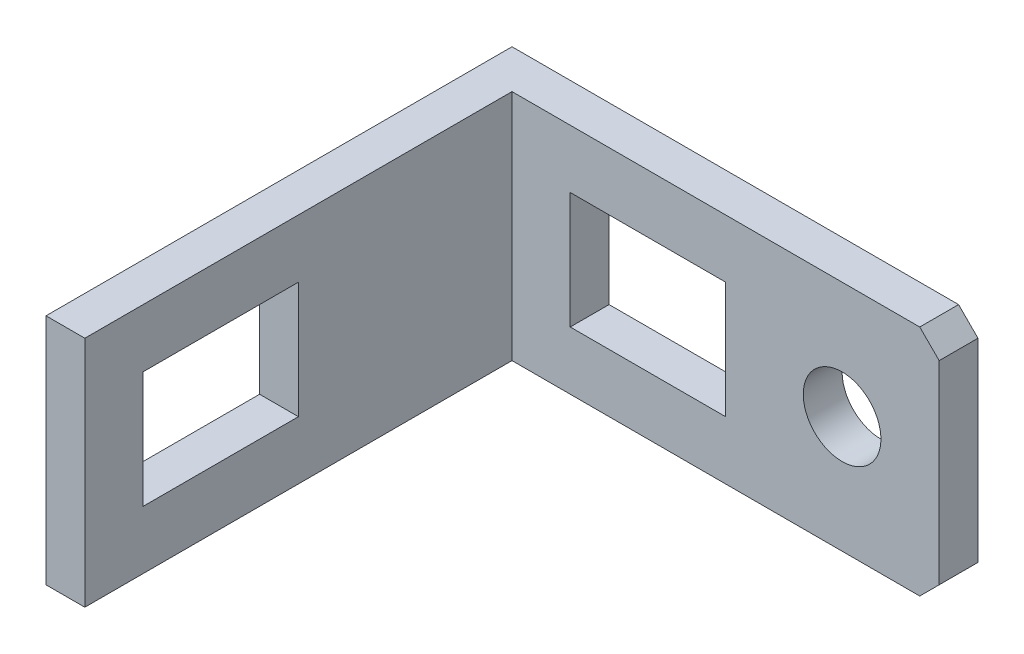
SolidWorks part; units mm, degrees
material "6061-T6 (SS)"
ref_plane "Front Plane" through (0, 0, 0) normal (0, 0, 1) x (1, 0, 0)
ref_plane "Top Plane" through (0, 0, 0) normal (0, 1, 0) x (1, 0, 0)
ref_plane "Right Plane" through (0, 0, 0) normal (1, 0, 0) x (0, 0, -1)
sketch "Sketch1" plane through (0, 0, 0) normal (0, 1, 0) x (1, 0, 0)
  line L1 (38.1, 3.175) -> (-38.1, 3.175)
  line L2 (38.1, 3.175) -> (38.1, -3.175)
  line L3 (38.1, -3.175) -> (-38.1, -3.175)
  line L4 (-38.1, 3.175) -> (-38.1, -3.175)
  line L5 (38.1, 3.175) -> (-38.1, -3.175) construction
  line L6 (38.1, -3.175) -> (-38.1, 3.175) construction
  line L7 (-31.75, -3.175) -> (-38.1, -3.175)
  line L8 (-31.75, -3.175) -> (-31.75, -73.025)
  line L9 (-31.75, -73.025) -> (-38.1, -73.025)
  line L10 (-38.1, -3.175) -> (-38.1, -73.025)
  line L11 (-31.75, -3.175) -> (-38.1, -73.025) construction
  line L12 (-31.75, -73.025) -> (-38.1, -3.175) construction
  point P0 (0, 0)
  point P6 (-34.925, -38.1)
  dimension "D1" = 76.2
  dimension "D2" = 76.2
  dimension "D3" = 6.35
  dimension "D4" = 6.35
extrude "Boss-Extrude1" add sketch "Sketch1" along normal mid plane 38.1 contours L3 L10 L9 L8 | L1 L4 L3 L2
sketch "Sketch2" plane through (0, 0, -3.175) normal (0, 0, -1) x (-1, 0, 0)
  line L0 (-38.1, 19.05) -> (38.1, 19.05) construction
  circle A0 centre (-22.225, 0) radius 6.35
  dimension "D1" = 12.7
  dimension "D2" = 22.225
  dimension "D3" = 19.05
extrude "Cut-Extrude1" cut sketch "Sketch2" against normal up to surface (6.35 mm away) up to face at (3.175, 0, 3.175)
sketch "Sketch3" plane through (0, 0, -3.175) normal (0, 0, -1) x (-1, 0, 0)
  line L1 (22.225, 9.525) -> (-3.175, 9.525)
  line L2 (22.225, 9.525) -> (22.225, -9.525)
  line L3 (22.225, -9.525) -> (-3.175, -9.525)
  line L4 (-3.175, 9.525) -> (-3.175, -9.525)
  line L5 (22.225, 9.525) -> (-3.175, -9.525) construction
  line L6 (22.225, -9.525) -> (-3.175, 9.525) construction
  point P0 (9.525, 0)
  dimension "D1" = 9.525
  dimension "D2" = 25.4
  dimension "D3" = 19.05
extrude "Cut-Extrude2" cut sketch "Sketch3" against normal up to surface (6.35 mm away) up to face at (28.575, 0, 3.175)
sketch "Sketch4" plane through (0, 0, -3.175) normal (0, 0, -1) x (-1, 0, 0)
  line L0 (-34.925, 19.05) -> (-38.1, 15.875)
  line L1 (-38.1, 19.05) -> (38.1, 19.05) construction
  line L2 (-38.1, 19.05) -> (-38.1, -19.05) construction
  line L3 (-38.1, 15.875) -> (-38.1, 19.05)
  line L4 (-38.1, 19.05) -> (-34.925, 19.05)
  line L5 (-34.925, -19.05) -> (-38.1, -15.875)
  line L6 (-38.1, -19.05) -> (38.1, -19.05) construction
  line L7 (-38.1, -15.875) -> (-38.1, -19.05)
  line L8 (-38.1, -19.05) -> (-34.925, -19.05)
  dimension "D1" = 3.175
  dimension "D2" = 3.175
  dimension "D3" = 3.175
  dimension "D4" = 3.175
extrude "Cut-Extrude3" cut sketch "Sketch4" against normal up to surface (6.35 mm away) up to face at (-9.525, 0, 3.175)
sketch "Sketch5" plane through (-31.75, 0, 0) normal (1, 0, 0) x (0, 0, -1)
  line L1 (-63.5, 9.525) -> (-38.1, 9.525)
  line L2 (-63.5, 9.525) -> (-63.5, -9.525)
  line L3 (-63.5, -9.525) -> (-38.1, -9.525)
  line L4 (-38.1, 9.525) -> (-38.1, -9.525)
  line L5 (-63.5, 9.525) -> (-38.1, -9.525) construction
  line L6 (-63.5, -9.525) -> (-38.1, 9.525) construction
  point P0 (-50.8, 0)
  dimension "D1" = 50.8
  dimension "D2" = 25.4
  dimension "D3" = 19.05
extrude "Cut-Extrude4" cut sketch "Sketch5" against normal up to surface (6.35 mm away) up to face at (-38.1, 0, 34.925)
